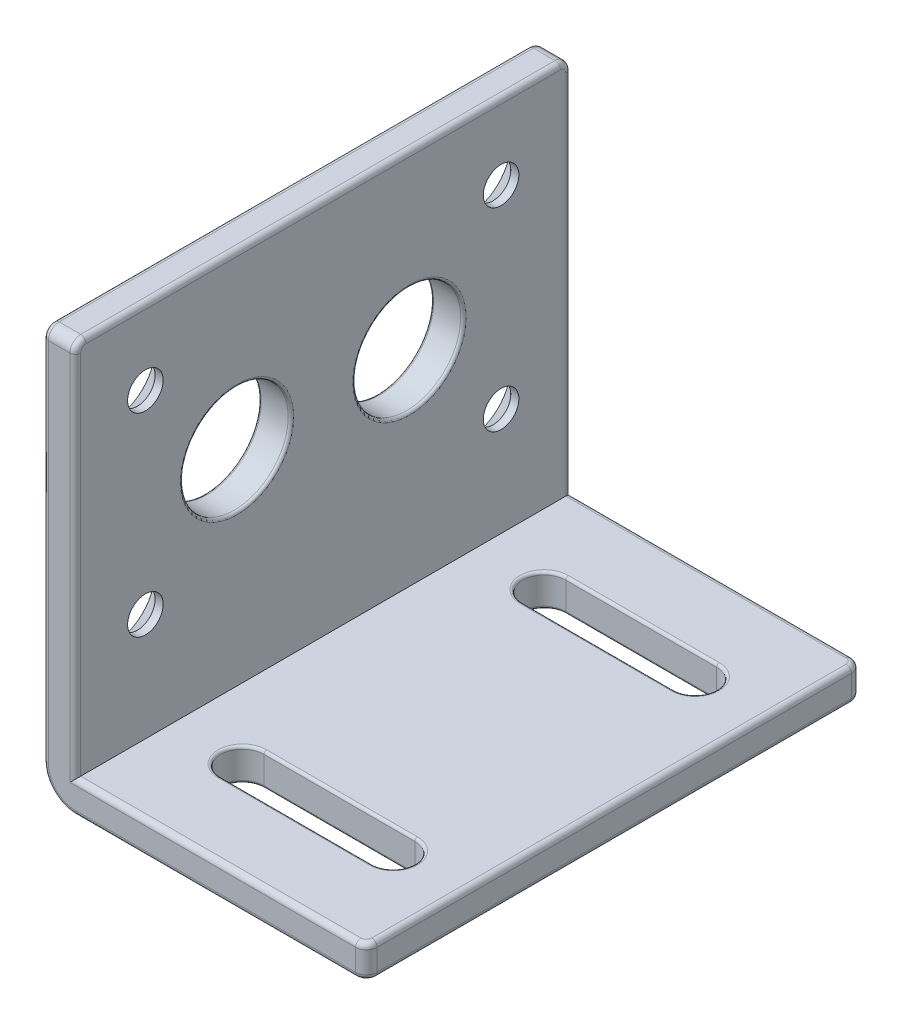
SolidWorks part; units mm, degrees
ref_plane "前视基准面" through (0, 0, 0) normal (0, 0, 1) x (1, 0, 0)
ref_plane "上视基准面" through (0, 0, 0) normal (0, 1, 0) x (1, 0, 0)
ref_plane "右视基准面" through (0, 0, 0) normal (1, 0, 0) x (0, 0, -1)
other "Configuration Table"
sketch "草图2" plane through (0, 0, 0) normal (0, 0, 1) x (1, 0, 0)
  line L0 (0, 0) -> (0, 38)
  line L1 (0, 38) -> (3, 38)
  line L2 (3, 38) -> (3, 3)
  line L3 (3, 3) -> (30, 3)
  line L4 (30, 3) -> (30, 0)
  line L5 (30, 0) -> (0, 0)
  dimension "D1" = 38
  dimension "D2" = 3
  dimension "D3" = 30
  dimension "D4" = 3
extrude "凸台-拉伸1" add sketch "草图2" against normal blind 46
sketch "草图3" plane through (0, 0, 0) normal (-1, 0, 0) x (0, 0, 1)
  line L0 (-23, 38) -> (-23, 0) construction
  line L1 (-31, 22) -> (-15, 22) construction
  line L2 (-39.5, 13) -> (-6.5, 13) construction
  line L3 (-39.5, 13) -> (-39.5, 31) construction
  line L4 (-39.5, 31) -> (-6.5, 31) construction
  line L5 (-6.5, 13) -> (-6.5, 31) construction
  line L6 (-39.5, 13) -> (-6.5, 31) construction
  line L7 (-39.5, 31) -> (-6.5, 13) construction
  line L8 (0, 0) -> (0, 38)
  line L9 (0, 38) -> (-46, 38)
  line L10 (-46, 38) -> (-46, 0)
  line L11 (-46, 0) -> (0, 0)
  line L12 (0, 0) -> (0, 38)
  line L13 (0, 38) -> (-46, 38)
  line L14 (-46, 38) -> (-46, 0)
  line L15 (-46, 0) -> (0, 0)
  circle A0 centre (-6.5, 31) radius 1.65
  circle A1 centre (-6.5, 13) radius 1.65
  circle A2 centre (-39.5, 13) radius 1.65
  circle A3 centre (-39.5, 31) radius 1.65
  circle A4 centre (-15, 22) radius 5
  circle A5 centre (-31, 22) radius 5
  point P5 (-23, 22)
  point P14 (-23, 22)
  dimension "D6" = 3.3
  dimension "D7" = 10
  dimension "D2" = 18
  dimension "D3" = 33
  dimension "D4" = 15
  dimension "D5" = 16
  dimension "D1" = 0
extrude "切除-拉伸1" cut sketch "草图3" against normal through all contours A3 | A5 | A2 | A4 | A1 | A0
chamfer "倒角2" distance 2.25 angle 45 4 edges at (0, 31, -4.85) (0, 13, -4.85) (0, 13, -37.85) (0, 31, -37.85)
sketch "草图4" plane through (0, 0, 0) normal (0, -1, 0) x (1, 0, 0)
  line L0 (0, -23) -> (30, -23) construction
  line L1 (16.5, 0) -> (16.5, -46) construction
  line L2 (9.5, -9) -> (23.5, -9) construction
  line L3 (9.5, -37) -> (23.5, -37) construction
  line L4 (30, 0) -> (0, 0)
  line L5 (0, 0) -> (0, -46)
  line L6 (0, -46) -> (30, -46)
  line L7 (30, -46) -> (30, 0)
  line L8 (30, 0) -> (0, 0)
  line L9 (0, 0) -> (0, -46)
  line L10 (0, -46) -> (30, -46)
  line L11 (30, -46) -> (30, 0)
  line L12 (9.5, -7) -> (23.5, -7)
  line L13 (9.5, -11) -> (23.5, -11)
  line L14 (9.5, -39) -> (23.5, -39)
  line L15 (9.5, -35) -> (23.5, -35)
  arc A0 (9.5, -7) -> (9.5, -11) centre (9.5, -9) ccw
  arc A1 (23.5, -11) -> (23.5, -7) centre (23.5, -9) ccw
  arc A2 (9.5, -39) -> (9.5, -35) centre (9.5, -37) cw
  arc A3 (23.5, -35) -> (23.5, -39) centre (23.5, -37) cw
  point P12 (16.5, -9)
  point P17 (16.5, -37)
  dimension "D2" = 14
  dimension "D3" = 4
  dimension "D4" = 14
  dimension "D5" = 6.5
  dimension "D1" = 0
extrude "切除-拉伸2" cut sketch "草图4" against normal through all contours A3 L15 A2 L14 | L13 A1 L12 A0
fillet "圆角1" radius 1 4 edges at (30, 1.5, -46) (30, 1.5, 0) (1.5, 38, -46) (1.5, 38, 0)
fillet "圆角2" radius 3 1 edges at (0, 0, -23)
fillet "圆角3" radius 0.5 22 edges at (3, 20, -46) (3, 37.7071, -45.7071) (3, 38, -23) (3, 37.7071, -0.2929) (16, 3, -46) (29.7071, 3, -45.7071) (30, 3, -23) (29.7071, 3, -0.2929) (0, 37.7071, -0.2929) (0, 38, -23) (0, 37.7071, -45.7071) (0, 20, -46) (0.8787, 0.8787, -46) (16, 0, -46) (29.7071, 0, -45.7071) (30, 0, -23) (29.7071, 0, -0.2929) (3, 20, 0) (16, 3, 0) (16, 0, 0) (0.8787, 0.8787, 0) (0, 20, 0)
fillet "圆角4" radius 0.25 20 edges at (7.5, 0, -9) (16.5, 0, -7) (25.5, 0, -9) (25.5, 3, -9) (16.5, 3, -7) (7.5, 3, -9) (16.5, 3, -35) (25.5, 3, -37) (25.5, 0, -37) (16.5, 0, -35) (16.5, 0, -11) (16.5, 3, -11) (16.5, 0, -39) (16.5, 3, -39) (7.5, 3, -37) (7.5, 0, -37) (0, 22, -26) (3, 27, -31) (0, 22, -10) (3, 27, -15)
